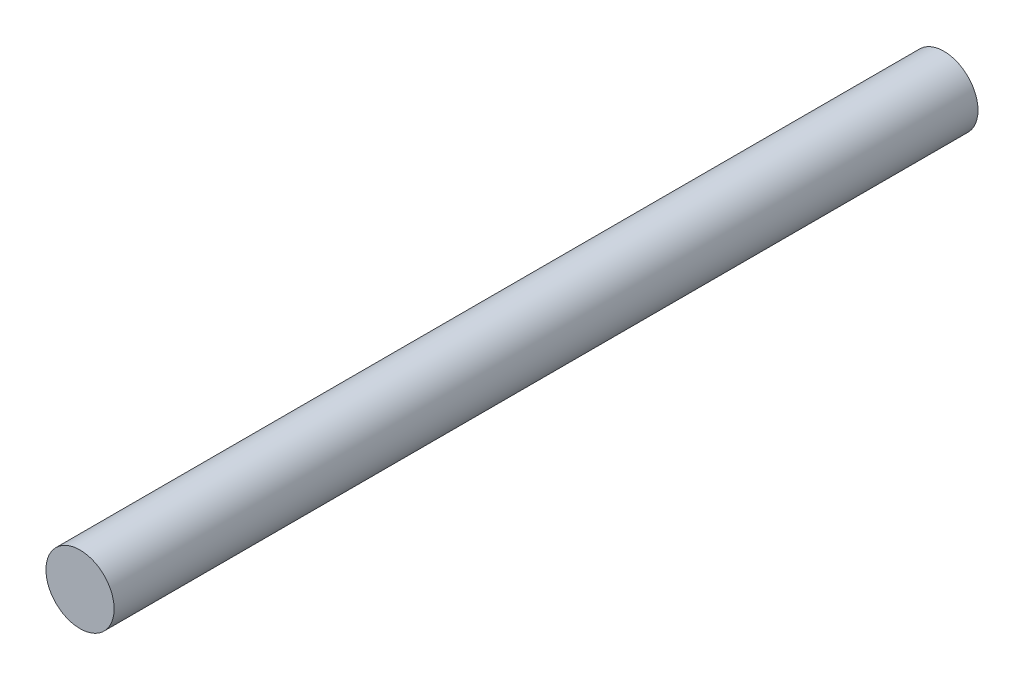
SolidWorks part; units mm, degrees
ref_plane "前基準面" through (0, 0, 0) normal (0, 0, 1) x (1, 0, 0)
ref_plane "上基準面" through (0, 0, 0) normal (0, 1, 0) x (1, 0, 0)
ref_plane "右基準面" through (0, 0, 0) normal (1, 0, 0) x (0, 0, -1)
sketch "草圖1" plane through (0, 0, 0) normal (0, 0, 1) x (1, 0, 0)
  circle A0 centre (0, 0) radius 1.5
  dimension "D1" = 3
extrude "伸長1" add sketch "草圖1" along normal mid plane 38
